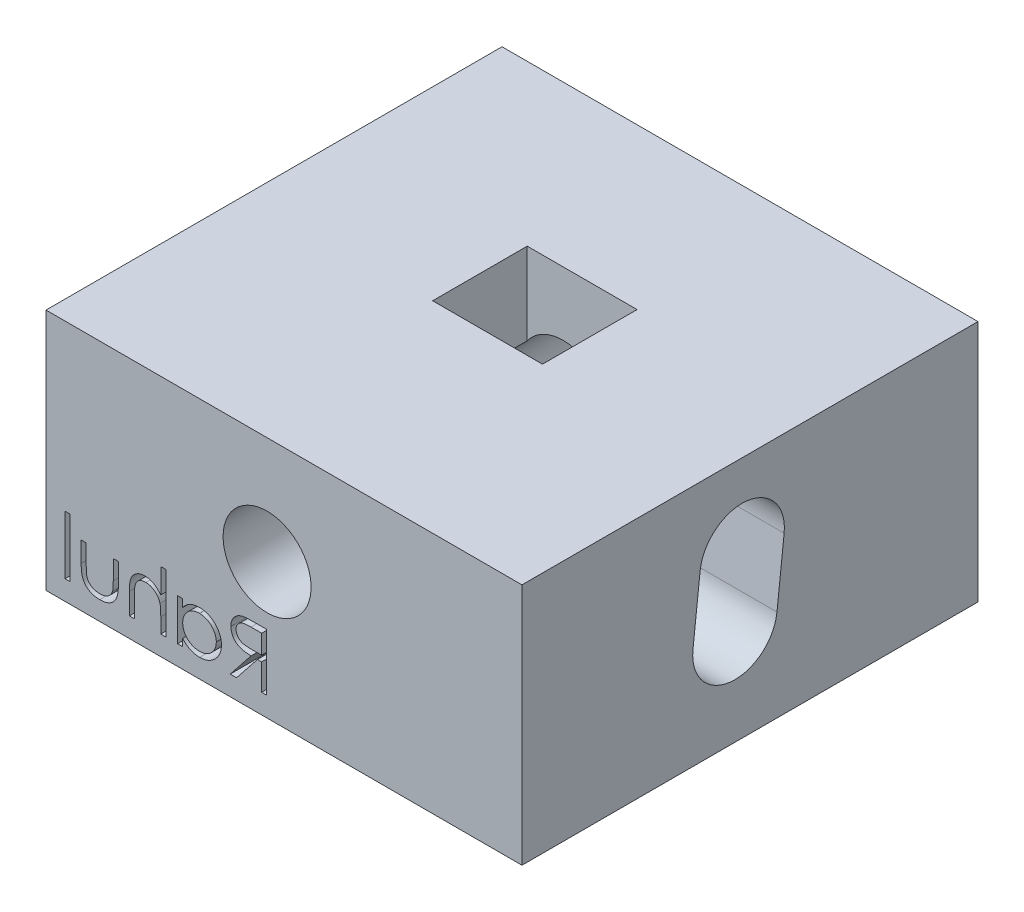
SolidWorks part; units mm, degrees
ref_plane "Front Plane" through (0, 0, 0) normal (0, 0, 1) x (1, 0, 0)
ref_plane "Top Plane" through (0, 0, 0) normal (0, 1, 0) x (1, 0, 0)
ref_plane "Right Plane" through (0, 0, 0) normal (1, 0, 0) x (0, 0, -1)
sketch "Sketch1" plane through (0, 0, 0) normal (0, 0, 1) x (1, 0, 0)
  line L1 (0, 0) -> (26.5101, 0)
  line L2 (0, 0) -> (0, 13.5256)
  line L3 (0, 13.5256) -> (26.5101, 13.5256)
  line L4 (26.5101, 0) -> (26.5101, 13.5256)
extrude "Boss-Extrude1" add sketch "Sketch1" along normal blind 25.4
sketch "Sketch2" plane through (0, 0, 0) normal (0, 0, 1) x (1, 0, 0)
  circle A0 centre (12.3139, 7.5328) radius 2.4514
  point P2 (-9.075, -0.3383)
extrude "Cut-Extrude1" cut sketch "Sketch2" along normal blind 38.608
sketch "Sketch3" plane through (0, 0, 0) normal (0, 1, 0) x (1, 0, 0)
  line L1 (10.3201, -8.9164) -> (16.4375, -8.9164)
  line L2 (10.3201, -8.9164) -> (10.3201, -14.1852)
  line L3 (10.3201, -14.1852) -> (16.4375, -14.1852)
  line L4 (16.4375, -8.9164) -> (16.4375, -14.1852)
extrude "Cut-Extrude2" cut sketch "Sketch3" against normal blind 38.608 and the other way blind 17.78
sketch "Sketch4" plane through (0, 0, 0) normal (-1, 0, 0) x (0, 0, 1)
  line L0 (13.5369, 5.3727) -> (13.1384, 8.9744) construction
  line L1 (11.1972, 5.1138) -> (10.7987, 8.7155)
  line L2 (15.8767, 5.6316) -> (15.4781, 9.2333)
  arc A0 (11.1972, 5.1138) -> (15.8767, 5.6316) centre (13.5369, 5.3727) ccw
  arc A1 (15.4781, 9.2333) -> (10.7987, 8.7155) centre (13.1384, 8.9744) ccw
  point P2 (13.3377, 7.1736)
extrude "Cut-Extrude3" cut sketch "Sketch4" against normal blind 89.154
sketch3d "3DSketch1"
  line L0 (23.9701, 10.9856, 0) -> (23.9701, 2.54, 0)
  line L1 (23.9701, 2.54, 0) -> (2.54, 2.54, 0)
  line L2 (2.54, 2.54, 0) -> (2.54, 10.9856, 0)
  line L3 (2.54, 10.9856, 0) -> (23.9701, 10.9856, 0)
  line L4 (23.9701, 10.9856, 0) -> (23.9701, 2.54, 0)
  line L5 (23.9701, 2.54, 0) -> (2.54, 2.54, 0)
  line L6 (2.54, 2.54, 0) -> (2.54, 10.9856, 0)
  line L7 (2.54, 10.9856, 0) -> (23.9701, 10.9856, 0)
  dimension "D1" = 2.54
sketch "Sketch5" plane through (0, 0, 0) normal (0, 0, -1) x (-1, 0, 0)
  text T0 "Rahul"
extrude "Cut-Extrude4" cut sketch "Sketch5" against normal blind 89.154
